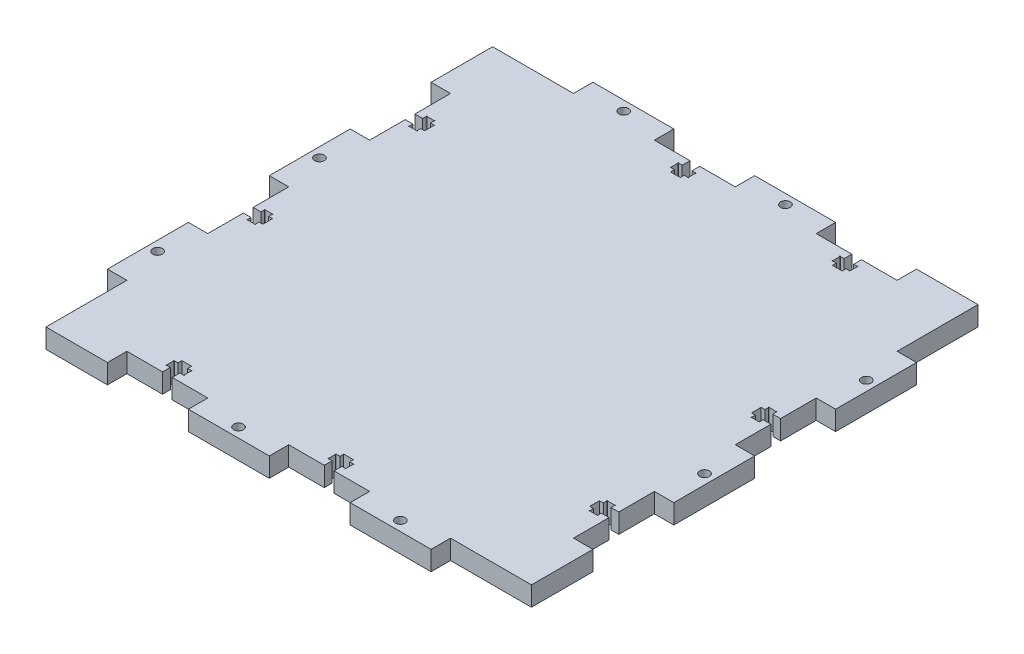
SolidWorks part; units mm, degrees
ref_plane "Front Plane" through (0, 0, 0) normal (0, 0, 1) x (1, 0, 0)
ref_plane "Top Plane" through (0, 0, 0) normal (0, 1, 0) x (1, 0, 0)
ref_plane "Right Plane" through (0, 0, 0) normal (1, 0, 0) x (0, 0, -1)
sketch "Sketch1" plane through (0, 0, 0) normal (0, 1, 0) x (1, 0, 0)
  line L0 (0, 75) -> (25, 75)
  line L1 (-50, 75) -> (-25, 75)
  line L2 (-75, 69) -> (-75, 50)
  line L3 (-69, -75) -> (-50, -75)
  line L4 (75, 50) -> (75, 25)
  line L7 (-75, 69) -> (-50, 69)
  line L8 (-50, 75) -> (-50, 69)
  line L10 (-25, 75) -> (-25, 69)
  line L11 (-25, 69) -> (0, 69)
  line L12 (0, 75) -> (0, 69)
  line L13 (50, 75) -> (69, 75)
  line L15 (25, 75) -> (25, 69)
  line L16 (25, 69) -> (50, 69)
  line L17 (50, 75) -> (50, 69)
  line L18 (75, 0) -> (75, -25)
  line L21 (75, 50) -> (69, 50)
  line L22 (69, 75) -> (69, 50)
  line L23 (75, 25) -> (69, 25)
  line L25 (75, 0) -> (69, 0)
  line L26 (69, 25) -> (69, 0)
  line L27 (75, -25) -> (69, -25)
  line L29 (75, -50) -> (69, -50)
  line L30 (69, -25) -> (69, -50)
  line L31 (75, -50) -> (75, -69)
  line L32 (25, -75) -> (50, -75)
  line L35 (75, -69) -> (50, -69)
  line L36 (50, -75) -> (50, -69)
  line L38 (25, -75) -> (25, -69)
  line L39 (25, -69) -> (0, -69)
  line L40 (0, -75) -> (0, -69)
  line L42 (-25, -75) -> (-25, -69)
  line L43 (-25, -69) -> (-50, -69)
  line L44 (-50, -75) -> (-50, -69)
  line L45 (-25, -75) -> (0, -75)
  line L46 (-75, 25) -> (-75, 0)
  line L49 (-75, -50) -> (-69, -50)
  line L50 (-69, -75) -> (-69, -50)
  line L51 (-75, -25) -> (-69, -25)
  line L53 (-75, 0) -> (-69, 0)
  line L54 (-69, -25) -> (-69, 0)
  line L55 (-75, 25) -> (-69, 25)
  line L57 (-75, 50) -> (-69, 50)
  line L58 (-69, 25) -> (-69, 50)
  line L59 (-75, -25) -> (-75, -50)
  dimension "D1" = 150
  dimension "D2" = 150
  dimension "D3" = 25
  dimension "D4" = 6
  dimension "D5" = 25
  dimension "25" = 25
  dimension "D6" = 25
  dimension "D7" = 6
  dimension "D8" = 6
  dimension "D9" = 25
  dimension "D10" = 25
  dimension "D11" = 6
  dimension "D12" = 25
  dimension "D13" = 6
  dimension "D14" = 25
  dimension "D15" = 25
  dimension "D16" = 6
  dimension "D17" = 25
  dimension "D18" = 19
  dimension "D19" = 6
  dimension "D20" = 25
  dimension "D21" = 25
  dimension "D22" = 25
  dimension "D23" = 6
  dimension "D24" = 6
  dimension "D25" = 25
  dimension "D26" = 25
  dimension "D27" = 19
  dimension "D28" = 6
  dimension "D29" = 25
  dimension "D30" = 25
  dimension "D31" = 6
  dimension "D32" = 25
  dimension "D33" = 25
  dimension "D34" = 6
  dimension "D35" = 25
  dimension "D36" = 19
extrude "Boss-Extrude1" add sketch "Sketch1" along normal blind 6
sketch "Sketch2" plane through (0, 6, 0) normal (0, 1, 0) x (1, 0, 0)
  line L0 (-25, 75) -> (-50, 75) construction
  line L1 (-25, 69) -> (-25, 75) construction
  line L2 (25, 75) -> (0, 75) construction
  line L3 (25, 69) -> (25, 75) construction
  line L4 (75, 25) -> (75, 50) construction
  line L5 (75, 50) -> (69, 50) construction
  line L6 (75, -25) -> (75, 0) construction
  line L7 (75, 0) -> (69, 0) construction
  line L8 (25, -75) -> (50, -75) construction
  line L9 (50, -75) -> (50, -69) construction
  line L10 (-25, -75) -> (0, -75) construction
  line L11 (0, -75) -> (0, -69) construction
  line L12 (-69, -25) -> (-75, -25) construction
  line L13 (-75, -25) -> (-75, -50) construction
  line L14 (-75, 25) -> (-75, 0) construction
  line L15 (-75, 0) -> (-69, 0) construction
  line L16 (-11, 69) -> (-14, 69)
  line L59 (0, 69) -> (-25, 69) construction
  line L60 (-14, 69) -> (-14, 66.6)
  line L61 (-14, 66.6) -> (-15.1, 66.6)
  line L63 (-15.2, 66.5) -> (-15.2, 64.3)
  line L65 (-15.1, 64.2) -> (-14, 64.2)
  line L66 (-14, 64.2) -> (-14, 63)
  line L67 (-14, 63) -> (-11, 63)
  line L69 (-12.5, 69) -> (-12.5, 63) construction
  line L72 (-11, 64.2) -> (-11, 63)
  line L73 (-9.9, 64.2) -> (-11, 64.2)
  line L74 (-9.8, 66.5) -> (-9.8, 64.3)
  line L75 (-11, 66.6) -> (-9.9, 66.6)
  line L76 (-11, 69) -> (-11, 66.6)
  line L91 (69, 11) -> (69, 14)
  line L92 (69, 14) -> (66.6, 14)
  line L93 (66.6, 14) -> (66.6, 15.1)
  line L94 (66.5, 15.2) -> (64.3, 15.2)
  line L95 (64.2, 15.1) -> (64.2, 14)
  line L96 (64.2, 14) -> (63, 14)
  line L97 (63, 14) -> (63, 11)
  line L98 (69, 12.5) -> (63, 12.5) construction
  line L99 (64.2, 11) -> (63, 11)
  line L100 (64.2, 9.9) -> (64.2, 11)
  line L101 (66.5, 9.8) -> (64.3, 9.8)
  line L102 (66.6, 11) -> (66.6, 9.9)
  line L103 (69, 11) -> (66.6, 11)
  line L104 (69, 0) -> (69, 25) construction
  line L105 (39, 69) -> (36, 69)
  line L106 (36, 69) -> (36, 66.6)
  line L107 (36, 66.6) -> (34.9, 66.6)
  line L108 (34.8, 66.5) -> (34.8, 64.3)
  line L109 (34.9, 64.2) -> (36, 64.2)
  line L110 (36, 64.2) -> (36, 63)
  line L111 (36, 63) -> (39, 63)
  line L112 (37.5, 69) -> (37.5, 63) construction
  line L113 (39, 64.2) -> (39, 63)
  line L114 (40.1, 64.2) -> (39, 64.2)
  line L115 (40.2, 66.5) -> (40.2, 64.3)
  line L116 (39, 66.6) -> (40.1, 66.6)
  line L117 (39, 69) -> (39, 66.6)
  line L118 (50, 69) -> (25, 69) construction
  line L119 (69, -39) -> (69, -36)
  line L120 (69, -36) -> (66.6, -36)
  line L121 (66.6, -36) -> (66.6, -34.9)
  line L122 (66.5, -34.8) -> (64.3, -34.8)
  line L123 (64.2, -34.9) -> (64.2, -36)
  line L124 (64.2, -36) -> (63, -36)
  line L125 (63, -36) -> (63, -39)
  line L126 (69, -37.5) -> (63, -37.5) construction
  line L127 (64.2, -39) -> (63, -39)
  line L128 (64.2, -40.1) -> (64.2, -39)
  line L129 (66.5, -40.2) -> (64.3, -40.2)
  line L130 (66.6, -39) -> (66.6, -40.1)
  line L131 (69, -39) -> (66.6, -39)
  line L132 (69, -50) -> (69, -25) construction
  line L133 (11, -69) -> (14, -69)
  line L134 (14, -69) -> (14, -66.6)
  line L135 (14, -66.6) -> (15.1, -66.6)
  line L136 (15.2, -66.5) -> (15.2, -64.3)
  line L137 (15.1, -64.2) -> (14, -64.2)
  line L138 (14, -64.2) -> (14, -63)
  line L139 (14, -63) -> (11, -63)
  line L140 (12.5, -69) -> (12.5, -63) construction
  line L141 (11, -64.2) -> (11, -63)
  line L142 (9.9, -64.2) -> (11, -64.2)
  line L143 (9.8, -66.5) -> (9.8, -64.3)
  line L144 (11, -66.6) -> (9.9, -66.6)
  line L145 (11, -69) -> (11, -66.6)
  line L146 (0, -69) -> (25, -69) construction
  line L147 (-39, -69) -> (-36, -69)
  line L148 (-36, -69) -> (-36, -66.6)
  line L149 (-36, -66.6) -> (-34.9, -66.6)
  line L150 (-34.8, -66.5) -> (-34.8, -64.3)
  line L151 (-34.9, -64.2) -> (-36, -64.2)
  line L152 (-36, -64.2) -> (-36, -63)
  line L153 (-36, -63) -> (-39, -63)
  line L154 (-37.5, -69) -> (-37.5, -63) construction
  line L155 (-39, -64.2) -> (-39, -63)
  line L156 (-40.1, -64.2) -> (-39, -64.2)
  line L157 (-40.2, -66.5) -> (-40.2, -64.3)
  line L158 (-39, -66.6) -> (-40.1, -66.6)
  line L159 (-39, -69) -> (-39, -66.6)
  line L160 (-50, -69) -> (-25, -69) construction
  line L161 (-69, 39) -> (-69, 36)
  line L162 (-69, 36) -> (-66.6, 36)
  line L163 (-66.6, 36) -> (-66.6, 34.9)
  line L164 (-66.5, 34.8) -> (-64.3, 34.8)
  line L165 (-64.2, 34.9) -> (-64.2, 36)
  line L166 (-64.2, 36) -> (-63, 36)
  line L167 (-63, 36) -> (-63, 39)
  line L168 (-69, 37.5) -> (-63, 37.5) construction
  line L169 (-64.2, 39) -> (-63, 39)
  line L170 (-64.2, 40.1) -> (-64.2, 39)
  line L171 (-66.5, 40.2) -> (-64.3, 40.2)
  line L172 (-66.6, 39) -> (-66.6, 40.1)
  line L173 (-69, 39) -> (-66.6, 39)
  line L174 (-69, 50) -> (-69, 25) construction
  line L175 (-69, -11) -> (-69, -14)
  line L176 (-69, -14) -> (-66.6, -14)
  line L177 (-66.6, -14) -> (-66.6, -15.1)
  line L178 (-66.5, -15.2) -> (-64.3, -15.2)
  line L179 (-64.2, -15.1) -> (-64.2, -14)
  line L180 (-64.2, -14) -> (-63, -14)
  line L181 (-63, -14) -> (-63, -11)
  line L182 (-69, -12.5) -> (-63, -12.5) construction
  line L183 (-64.2, -11) -> (-63, -11)
  line L184 (-64.2, -9.9) -> (-64.2, -11)
  line L185 (-66.5, -9.8) -> (-64.3, -9.8)
  line L186 (-66.6, -11) -> (-66.6, -9.9)
  line L187 (-69, -11) -> (-66.6, -11)
  line L188 (-69, 0) -> (-69, -25) construction
  circle A0 centre (-37.5, 72) radius 1.5
  circle A1 centre (12.5, 72) radius 1.5
  circle A2 centre (72, 37.5) radius 1.5
  circle A3 centre (72, -12.5) radius 1.5
  circle A4 centre (37.5, -72) radius 1.5
  circle A5 centre (-12.5, -72) radius 1.5
  circle A6 centre (-72, -37.5) radius 1.5
  circle A7 centre (-72, 12.5) radius 1.5
  arc A9 (-15.1, 66.6) -> (-15.2, 66.5) centre (-15.2, 66.6) ccw
  arc A10 (-15.2, 64.3) -> (-15.1, 64.2) centre (-15.2, 64.2) ccw
  arc A11 (-9.8, 64.3) -> (-9.9, 64.2) centre (-9.8, 64.2) cw
  arc A12 (-9.9, 66.6) -> (-9.8, 66.5) centre (-9.8, 66.6) cw
  arc A17 (66.6, 15.1) -> (66.5, 15.2) centre (66.6, 15.2) ccw
  arc A18 (64.3, 15.2) -> (64.2, 15.1) centre (64.2, 15.2) ccw
  arc A19 (64.3, 9.8) -> (64.2, 9.9) centre (64.2, 9.8) cw
  arc A20 (66.6, 9.9) -> (66.5, 9.8) centre (66.6, 9.8) cw
  arc A21 (34.9, 66.6) -> (34.8, 66.5) centre (34.8, 66.6) ccw
  arc A22 (34.8, 64.3) -> (34.9, 64.2) centre (34.8, 64.2) ccw
  arc A23 (40.2, 64.3) -> (40.1, 64.2) centre (40.2, 64.2) cw
  arc A24 (40.1, 66.6) -> (40.2, 66.5) centre (40.2, 66.6) cw
  arc A25 (66.6, -34.9) -> (66.5, -34.8) centre (66.6, -34.8) ccw
  arc A26 (64.3, -34.8) -> (64.2, -34.9) centre (64.2, -34.8) ccw
  arc A27 (64.3, -40.2) -> (64.2, -40.1) centre (64.2, -40.2) cw
  arc A28 (66.6, -40.1) -> (66.5, -40.2) centre (66.6, -40.2) cw
  arc A29 (15.1, -66.6) -> (15.2, -66.5) centre (15.2, -66.6) ccw
  arc A30 (15.2, -64.3) -> (15.1, -64.2) centre (15.2, -64.2) ccw
  arc A31 (9.8, -64.3) -> (9.9, -64.2) centre (9.8, -64.2) cw
  arc A32 (9.9, -66.6) -> (9.8, -66.5) centre (9.8, -66.6) cw
  arc A33 (-34.9, -66.6) -> (-34.8, -66.5) centre (-34.8, -66.6) ccw
  arc A34 (-34.8, -64.3) -> (-34.9, -64.2) centre (-34.8, -64.2) ccw
  arc A35 (-40.2, -64.3) -> (-40.1, -64.2) centre (-40.2, -64.2) cw
  arc A36 (-40.1, -66.6) -> (-40.2, -66.5) centre (-40.2, -66.6) cw
  arc A37 (-66.6, 34.9) -> (-66.5, 34.8) centre (-66.6, 34.8) ccw
  arc A38 (-64.3, 34.8) -> (-64.2, 34.9) centre (-64.2, 34.8) ccw
  arc A39 (-64.3, 40.2) -> (-64.2, 40.1) centre (-64.2, 40.2) cw
  arc A40 (-66.6, 40.1) -> (-66.5, 40.2) centre (-66.6, 40.2) cw
  arc A41 (-66.6, -15.1) -> (-66.5, -15.2) centre (-66.6, -15.2) ccw
  arc A42 (-64.3, -15.2) -> (-64.2, -15.1) centre (-64.2, -15.2) ccw
  arc A43 (-64.3, -9.8) -> (-64.2, -9.9) centre (-64.2, -9.8) cw
  arc A44 (-66.6, -9.9) -> (-66.5, -9.8) centre (-66.6, -9.8) cw
  point P48 (0, 0)
  point P83 (-12.5, 69)
  point P104 (69, 12.5)
  point P122 (37.5, 69)
  point P148 (69, -37.5)
  point P174 (12.5, -69)
  point P196 (-37.5, -69)
  point P222 (-69, 37.5)
  point P246 (-69, -12.5)
  point P247 (0, 0)
  dimension "D1" = 3
  dimension "D3" = 3
  dimension "D5" = 3
  dimension "D7" = 3
  dimension "D9" = 3
  dimension "D11" = 3
  dimension "D13" = 12.5
  dimension "D15" = 3
  dimension "D32" = 3
  dimension "D31" = 3
  dimension "D17" = 3
  dimension "D29" = 3
  dimension "D30" = 3
  dimension "D33" = 3
  dimension "D34" = 3
  dimension "D35" = 3
  dimension "D36" = 3
  dimension "D2" = 12.5
  dimension "D4" = 12.5
  dimension "D6" = 12.5
  dimension "D8" = 12.5
  dimension "D10" = 12.5
  dimension "D12" = 12.5
  dimension "D14" = 3
  dimension "D16" = 12.5
  dimension "D18" = 6
  dimension "D19" = 5.4
  dimension "D20" = 2.4
  dimension "D21" = 1.2
  dimension "D22" = 0.1
  dimension "D23" = 3
  dimension "D24" = 6
  dimension "D25" = 5.4
  dimension "D26" = 2.4
  dimension "D27" = 1.2
  dimension "D28" = 0.1
  dimension "D37" = 3
  dimension "D38" = 6
  dimension "D39" = 5.4
  dimension "D40" = 2.4
  dimension "D41" = 1.2
  dimension "D42" = 0.1
  dimension "D43" = 3
  dimension "D44" = 6
  dimension "D45" = 5.4
  dimension "D46" = 2.4
  dimension "D47" = 1.2
  dimension "D48" = 0.1
  dimension "D49" = 3
  dimension "D50" = 6
  dimension "D51" = 5.4
  dimension "D52" = 2.4
  dimension "D53" = 1.2
  dimension "D54" = 0.1
  dimension "D55" = 3
  dimension "D56" = 6
  dimension "D57" = 5.4
  dimension "D58" = 2.4
  dimension "D59" = 1.2
  dimension "D60" = 0.1
  dimension "D61" = 3
  dimension "D62" = 6
  dimension "D63" = 5.4
  dimension "D64" = 2.4
  dimension "D65" = 1.2
  dimension "D66" = 0.1
  dimension "D67" = 3
  dimension "D68" = 6
  dimension "D69" = 5.4
  dimension "D70" = 2.4
  dimension "D71" = 1.2
  dimension "D72" = 0.1
extrude "Cut-Extrude1" cut sketch "Sketch2" against normal through all
